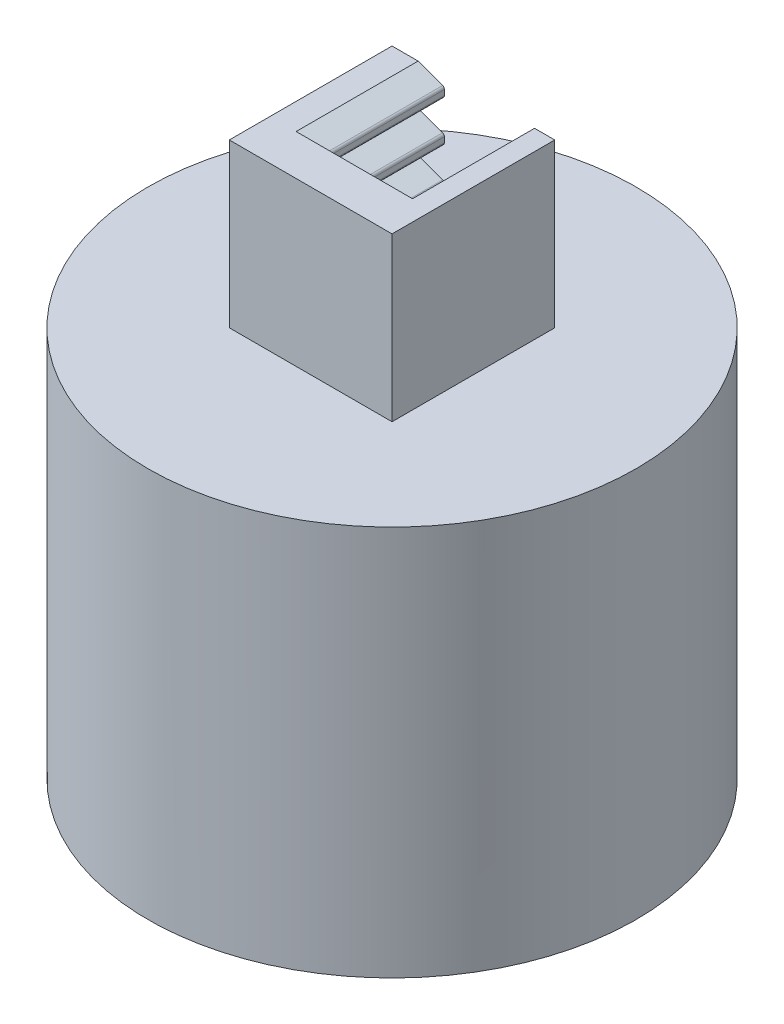
SolidWorks part; units mm, degrees
ref_plane "Front Plane" through (0, 0, 0) normal (0, 0, 1) x (1, 0, 0)
ref_plane "Top Plane" through (0, 0, 0) normal (0, 1, 0) x (1, 0, 0)
ref_plane "Right Plane" through (0, 0, 0) normal (1, 0, 0) x (0, 0, -1)
sketch "Sketch1" plane through (0, 0, 0) normal (0, 1, 0) x (1, 0, 0)
  circle A0 centre (0, 0) radius 15
  circle A1 centre (0, 0) radius 13
  dimension "D1" = 26
  dimension "D2" = 30
extrude "Boss-Extrude1" add sketch "Sketch1" along normal blind 20
sketch "Sketch2" plane through (0, 20, 0) normal (0, 1, 0) x (1, 0, 0)
  circle A0 centre (0, 0) radius 15
extrude "Boss-Extrude2" add sketch "Sketch2" along normal blind 4
sketch "Sketch4" plane through (0, 24, 0) normal (0, 1, 0) x (1, 0, 0)
  line L0 (0, 5) -> (0, -5) construction
  line L1 (-5, 5) -> (5, 5)
  line L2 (-5, 5) -> (-5, -5)
  line L3 (-5, -5) -> (5, -5)
  line L4 (5, 5) -> (5, -5)
  line L5 (-5, 0) -> (5, 0) construction
  dimension "D1" = 10
  dimension "D2" = 10
extrude "Boss-Extrude3" add sketch "Sketch4" along normal blind 10
sketch "Sketch6" plane through (0, 0, -5) normal (0, 0, -1) x (-1, 0, 0)
  line L1 (-5, 34) -> (5, 34) construction
  line L3 (-3.7584, 34) -> (3.3958, 34)
  line L4 (-3.7584, 24) -> (3.5416, 24)
  line L405 (2.1355, 274) -> (0.2416, 274)
  line L406 (0.2416, 274) -> (0.2416, 34)
  line L407 (0.2416, 34) -> (-1.7584, 34)
  line L408 (-1.7584, 34) -> (-1.7584, 274)
  line L409 (-1.7584, 274) -> (-3.7584, 274)
  line L410 (-3.7584, 274) -> (-3.7584, 24)
  line L411 (-3.7584, 24) -> (3.5416, 24)
  line L412 (3.5416, 24) -> (3.5416, 24.6743)
  line L413 (3.5416, 24.6743) -> (1.8918, 25.2748)
  line L414 (1.7816, 25.432) -> (1.7816, 25.7555)
  line L415 (1.8918, 25.9128) -> (3.5416, 26.5133)
  line L416 (3.5416, 26.5133) -> (3.5416, 27.1876)
  line L417 (3.5416, 27.1876) -> (1.8918, 27.7881)
  line L418 (1.7816, 27.9453) -> (1.7816, 28.2688)
  line L419 (1.8918, 28.426) -> (3.5416, 29.0265)
  line L420 (3.5416, 29.0265) -> (3.5416, 29.7008)
  line L421 (3.5416, 29.7008) -> (1.8918, 30.3013)
  line L422 (1.7816, 30.4586) -> (1.7816, 30.7821)
  line L423 (1.8918, 30.9393) -> (3.5416, 31.5398)
  line L424 (3.5416, 31.5398) -> (3.5416, 32.2141)
  line L425 (3.5416, 32.2141) -> (1.8918, 32.8146)
  line L426 (1.7816, 32.9719) -> (1.7816, 33.2953)
  line L427 (1.8918, 33.4526) -> (3.5416, 34.0531)
  line L428 (3.5416, 34.0531) -> (3.5416, 34.7274)
  line L429 (3.5416, 34.7274) -> (1.8918, 35.3279)
  line L430 (1.7816, 35.4851) -> (1.7816, 35.8086)
  line L431 (1.8918, 35.9658) -> (3.5416, 36.5664)
  line L432 (3.5416, 36.5664) -> (3.5416, 37.2406)
  line L433 (3.5416, 37.2406) -> (1.8918, 37.8412)
  line L434 (1.7816, 37.9984) -> (1.7816, 38.3219)
  line L435 (1.8918, 38.4791) -> (3.5416, 39.0796)
  line L436 (3.5416, 39.0796) -> (3.5416, 39.7539)
  line L437 (3.5416, 39.7539) -> (1.8918, 40.3544)
  line L438 (1.7816, 40.5117) -> (1.7816, 40.8351)
  line L439 (1.8918, 40.9924) -> (3.5416, 41.5929)
  line L440 (3.5416, 41.5929) -> (3.5416, 42.2672)
  line L441 (3.5416, 42.2672) -> (1.8918, 42.8677)
  line L442 (1.7816, 43.025) -> (1.7816, 43.3484)
  line L443 (1.8918, 43.5057) -> (3.5416, 44.1062)
  line L444 (3.5416, 44.1062) -> (3.5416, 44.7805)
  line L445 (3.5416, 44.7805) -> (1.8918, 45.381)
  line L446 (1.7816, 45.5382) -> (1.7816, 45.8617)
  line L447 (1.8918, 46.0189) -> (3.5416, 46.6194)
  line L448 (3.5416, 46.6194) -> (3.5416, 47.2937)
  line L449 (3.5416, 47.2937) -> (1.8918, 47.8942)
  line L450 (1.7816, 48.0515) -> (1.7816, 48.375)
  line L451 (1.8918, 48.5322) -> (3.5416, 49.1327)
  line L452 (3.5416, 49.1327) -> (3.5416, 49.807)
  line L453 (3.5416, 49.807) -> (1.8918, 50.4075)
  line L454 (1.7816, 50.5648) -> (1.7816, 50.8882)
  line L455 (1.8918, 51.0455) -> (3.5416, 51.646)
  line L456 (3.5416, 51.646) -> (3.5416, 52.3203)
  line L457 (3.5416, 52.3203) -> (1.8918, 52.9208)
  line L458 (1.7816, 53.078) -> (1.7816, 53.4015)
  line L459 (1.8918, 53.5588) -> (3.5416, 54.1593)
  line L460 (3.5416, 54.1593) -> (3.5416, 54.8335)
  line L461 (3.5416, 54.8335) -> (1.8918, 55.4341)
  line L462 (1.7816, 55.5913) -> (1.7816, 55.9148)
  line L463 (1.8918, 56.072) -> (3.5416, 56.6725)
  line L464 (3.5416, 56.6725) -> (3.5416, 57.3468)
  line L465 (3.5416, 57.3468) -> (1.8918, 57.9473)
  line L466 (1.7816, 58.1046) -> (1.7816, 58.428)
  line L467 (1.8918, 58.5853) -> (3.5416, 59.1858)
  line L468 (3.5416, 59.1858) -> (3.5416, 59.8601)
  line L469 (3.5416, 59.8601) -> (1.8918, 60.4606)
  line L470 (1.7816, 60.6179) -> (1.7816, 60.9413)
  line L471 (1.8918, 61.0986) -> (3.5416, 61.6991)
  line L472 (3.5416, 61.6991) -> (3.5416, 62.3734)
  line L473 (3.5416, 62.3734) -> (1.8918, 62.9739)
  line L474 (1.7816, 63.1311) -> (1.7816, 63.4546)
  line L475 (1.8918, 63.6118) -> (3.5416, 64.2124)
  line L476 (3.5416, 64.2124) -> (3.5416, 64.8866)
  line L477 (3.5416, 64.8866) -> (1.8918, 65.4871)
  line L478 (1.7816, 65.6444) -> (1.7816, 65.9679)
  line L479 (1.8918, 66.1251) -> (3.5416, 66.7256)
  line L480 (3.5416, 66.7256) -> (3.5416, 67.3999)
  line L481 (3.5416, 67.3999) -> (1.8918, 68.0004)
  line L482 (1.7816, 68.1577) -> (1.7816, 68.4811)
  line L483 (1.8918, 68.6384) -> (3.5416, 69.2389)
  line L484 (3.5416, 69.2389) -> (3.5416, 69.9132)
  line L485 (3.5416, 69.9132) -> (1.8918, 70.5137)
  line L486 (1.7816, 70.6709) -> (1.7816, 70.9944)
  line L487 (1.8918, 71.1517) -> (3.5416, 71.7522)
  line L488 (3.5416, 71.7522) -> (3.5416, 72.4265)
  line L489 (3.5416, 72.4265) -> (1.8918, 73.027)
  line L490 (1.7816, 73.1842) -> (1.7816, 73.5077)
  line L491 (1.8918, 73.6649) -> (3.5416, 74.2654)
  line L492 (3.5416, 74.2654) -> (3.5416, 74.9397)
  line L493 (3.5416, 74.9397) -> (1.8918, 75.5402)
  line L494 (1.7816, 75.6975) -> (1.7816, 76.0209)
  line L495 (1.8918, 76.1782) -> (3.5416, 76.7787)
  line L496 (3.5416, 76.7787) -> (3.5416, 77.453)
  line L497 (3.5416, 77.453) -> (1.8918, 78.0535)
  line L498 (1.7816, 78.2108) -> (1.7816, 78.5342)
  line L499 (1.8918, 78.6915) -> (3.5416, 79.292)
  line L500 (3.5416, 79.292) -> (3.5416, 79.9663)
  line L501 (3.5416, 79.9663) -> (1.8918, 80.5668)
  line L502 (1.7816, 80.724) -> (1.7816, 81.0475)
  line L503 (1.8918, 81.2047) -> (3.5416, 81.8053)
  line L504 (3.5416, 81.8053) -> (3.5416, 82.4795)
  line L505 (3.5416, 82.4795) -> (1.8918, 83.0801)
  line L506 (1.7816, 83.2373) -> (1.7816, 83.5608)
  line L507 (1.8918, 83.718) -> (3.5416, 84.3185)
  line L508 (3.5416, 84.3185) -> (3.5416, 84.9928)
  line L509 (3.5416, 84.9928) -> (1.8918, 85.5933)
  line L510 (1.7816, 85.7506) -> (1.7816, 86.074)
  line L511 (1.8918, 86.2313) -> (3.5416, 86.8318)
  line L512 (3.5416, 86.8318) -> (3.5416, 87.5061)
  line L513 (3.5416, 87.5061) -> (1.8918, 88.1066)
  line L514 (1.7816, 88.2638) -> (1.7816, 88.5873)
  line L515 (1.8918, 88.7446) -> (3.5416, 89.3451)
  line L516 (3.5416, 89.3451) -> (3.5416, 90.0194)
  line L517 (3.5416, 90.0194) -> (1.8918, 90.6199)
  line L518 (1.7816, 90.7771) -> (1.7816, 91.1006)
  line L519 (1.8918, 91.2578) -> (3.5416, 91.8583)
  line L520 (3.5416, 91.8583) -> (3.5416, 92.5326)
  line L521 (3.5416, 92.5326) -> (1.8918, 93.1331)
  line L522 (1.7816, 93.2904) -> (1.7816, 93.6139)
  line L523 (1.8918, 93.7711) -> (3.5416, 94.3716)
  line L524 (3.5416, 94.3716) -> (3.5416, 95.0459)
  line L525 (3.5416, 95.0459) -> (1.8918, 95.6464)
  line L526 (1.7816, 95.8037) -> (1.7816, 96.1271)
  line L527 (1.8918, 96.2844) -> (3.5416, 96.8849)
  line L528 (3.5416, 96.8849) -> (3.5416, 97.5592)
  line L529 (3.5416, 97.5592) -> (1.8918, 98.1597)
  line L530 (1.7816, 98.3169) -> (1.7816, 98.6404)
  line L531 (1.8918, 98.7976) -> (3.5416, 99.3982)
  line L532 (3.5416, 99.3982) -> (3.5416, 100.0724)
  line L533 (3.5416, 100.0724) -> (1.8918, 100.673)
  line L534 (1.7816, 100.8302) -> (1.7816, 101.1537)
  line L535 (1.8918, 101.3109) -> (3.5416, 101.9114)
  line L536 (3.5416, 101.9114) -> (3.5416, 102.5857)
  line L537 (3.5416, 102.5857) -> (1.8918, 103.1862)
  line L538 (1.7816, 103.3435) -> (1.7816, 103.6669)
  line L539 (1.8918, 103.8242) -> (3.5416, 104.4247)
  line L540 (3.5416, 104.4247) -> (3.5416, 105.099)
  line L541 (3.5416, 105.099) -> (1.8918, 105.6995)
  line L542 (1.7816, 105.8568) -> (1.7816, 106.1802)
  line L543 (1.8918, 106.3375) -> (3.5416, 106.938)
  line L544 (3.5416, 106.938) -> (3.5416, 107.6123)
  line L545 (3.5416, 107.6123) -> (1.8918, 108.2128)
  line L546 (1.7816, 108.37) -> (1.7816, 108.6935)
  line L547 (1.8918, 108.8507) -> (3.5416, 109.4512)
  line L548 (3.5416, 109.4512) -> (3.5416, 110.1255)
  line L549 (3.5416, 110.1255) -> (1.8918, 110.726)
  line L550 (1.7816, 110.8833) -> (1.7816, 111.2068)
  line L551 (1.8918, 111.364) -> (3.5416, 111.9645)
  line L552 (3.5416, 111.9645) -> (3.5416, 112.6388)
  line L553 (3.5416, 112.6388) -> (1.8918, 113.2393)
  line L554 (1.7816, 113.3966) -> (1.7816, 113.72)
  line L555 (1.8918, 113.8773) -> (3.5416, 114.4778)
  line L556 (3.5416, 114.4778) -> (3.5416, 115.1521)
  line L557 (3.5416, 115.1521) -> (1.8918, 115.7526)
  line L558 (1.7816, 115.9098) -> (1.7816, 116.2333)
  line L559 (1.8918, 116.3906) -> (3.5416, 116.9911)
  line L560 (3.5416, 116.9911) -> (3.5416, 117.6653)
  line L561 (3.5416, 117.6653) -> (1.8918, 118.2659)
  line L562 (1.7816, 118.4231) -> (1.7816, 118.7466)
  line L563 (1.8918, 118.9038) -> (3.5416, 119.5043)
  line L564 (3.5416, 119.5043) -> (3.5416, 120.1786)
  line L565 (3.5416, 120.1786) -> (1.8918, 120.7791)
  line L566 (1.7816, 120.9364) -> (1.7816, 121.2598)
  line L567 (1.8918, 121.4171) -> (3.5416, 122.0176)
  line L568 (3.5416, 122.0176) -> (3.5416, 122.6919)
  line L569 (3.5416, 122.6919) -> (1.8918, 123.2924)
  line L570 (1.7816, 123.4497) -> (1.7816, 123.7731)
  line L571 (1.8918, 123.9304) -> (3.5416, 124.5309)
  line L572 (3.5416, 124.5309) -> (3.5416, 125.2052)
  line L573 (3.5416, 125.2052) -> (1.8918, 125.8057)
  line L574 (1.7816, 125.9629) -> (1.7816, 126.2864)
  line L575 (1.8918, 126.4436) -> (3.5416, 127.0442)
  line L576 (3.5416, 127.0442) -> (3.5416, 127.7184)
  line L577 (3.5416, 127.7184) -> (1.8918, 128.3189)
  line L578 (1.7816, 128.4762) -> (1.7816, 128.7997)
  line L579 (1.8918, 128.9569) -> (3.5416, 129.5574)
  line L580 (3.5416, 129.5574) -> (3.5416, 130.2317)
  line L581 (3.5416, 130.2317) -> (1.8918, 130.8322)
  line L582 (1.7816, 130.9895) -> (1.7816, 131.3129)
  line L583 (1.8918, 131.4702) -> (3.5416, 132.0707)
  line L584 (3.5416, 132.0707) -> (3.5416, 132.745)
  line L585 (3.5416, 132.745) -> (1.8918, 133.3455)
  line L586 (1.7816, 133.5027) -> (1.7816, 133.8262)
  line L587 (1.8918, 133.9835) -> (3.5416, 134.584)
  line L588 (3.5416, 134.584) -> (3.5416, 135.2583)
  line L589 (3.5416, 135.2583) -> (1.8918, 135.8588)
  line L590 (1.7816, 136.016) -> (1.7816, 136.3395)
  line L591 (1.8918, 136.4967) -> (3.5416, 137.0972)
  line L592 (3.5416, 137.0972) -> (3.5416, 137.7715)
  line L593 (3.5416, 137.7715) -> (1.8918, 138.372)
  line L594 (1.7816, 138.5293) -> (1.7816, 138.8527)
  line L595 (1.8918, 139.01) -> (3.5416, 139.6105)
  line L596 (3.5416, 139.6105) -> (3.5416, 140.2848)
  line L597 (3.5416, 140.2848) -> (1.8918, 140.8853)
  line L598 (1.7816, 141.0426) -> (1.7816, 141.366)
  line L599 (1.8918, 141.5233) -> (3.5416, 142.1238)
  line L600 (3.5416, 142.1238) -> (3.5416, 142.7981)
  line L601 (3.5416, 142.7981) -> (1.8918, 143.3986)
  line L602 (1.7816, 143.5558) -> (1.7816, 143.8793)
  line L603 (1.8918, 144.0365) -> (3.5416, 144.6371)
  line L604 (3.5416, 144.6371) -> (3.5416, 145.3113)
  line L605 (3.5416, 145.3113) -> (1.8918, 145.9119)
  line L606 (1.7816, 146.0691) -> (1.7816, 146.3926)
  line L607 (1.8918, 146.5498) -> (3.5416, 147.1503)
  line L608 (3.5416, 147.1503) -> (3.5416, 147.8246)
  line L609 (3.5416, 147.8246) -> (1.8918, 148.4251)
  line L610 (1.7816, 148.5824) -> (1.7816, 148.9058)
  line L611 (1.8918, 149.0631) -> (3.5416, 149.6636)
  line L612 (3.5416, 149.6636) -> (3.5416, 150.3379)
  line L613 (3.5416, 150.3379) -> (1.8918, 150.9384)
  line L614 (1.7816, 151.0956) -> (1.7816, 151.4191)
  line L615 (1.8918, 151.5764) -> (3.5416, 152.1769)
  line L616 (3.5416, 152.1769) -> (3.5416, 152.8512)
  line L617 (3.5416, 152.8512) -> (1.8918, 153.4517)
  line L618 (1.7816, 153.6089) -> (1.7816, 153.9324)
  line L619 (1.8918, 154.0896) -> (3.5416, 154.6901)
  line L620 (3.5416, 154.6901) -> (3.5416, 155.3644)
  line L621 (3.5416, 155.3644) -> (1.8918, 155.9649)
  line L622 (1.7816, 156.1222) -> (1.7816, 156.4457)
  line L623 (1.8918, 156.6029) -> (3.5416, 157.2034)
  line L624 (3.5416, 157.2034) -> (3.5416, 157.8777)
  line L625 (3.5416, 157.8777) -> (1.8918, 158.4782)
  line L626 (1.7816, 158.6355) -> (1.7816, 158.9589)
  line L627 (1.8918, 159.1162) -> (3.5416, 159.7167)
  line L628 (3.5416, 159.7167) -> (3.5416, 160.391)
  line L629 (3.5416, 160.391) -> (1.8918, 160.9915)
  line L630 (1.7816, 161.1487) -> (1.7816, 161.4722)
  line L631 (1.8918, 161.6294) -> (3.5416, 162.23)
  line L632 (3.5416, 162.23) -> (3.5416, 162.9042)
  line L633 (3.5416, 162.9042) -> (1.8918, 163.5048)
  line L634 (1.7816, 163.662) -> (1.7816, 163.9855)
  line L635 (1.8918, 164.1427) -> (3.5416, 164.7432)
  line L636 (3.5416, 164.7432) -> (3.5416, 165.4175)
  line L637 (3.5416, 165.4175) -> (1.8918, 166.018)
  line L638 (1.7816, 166.1753) -> (1.7816, 166.4987)
  line L639 (1.8918, 166.656) -> (3.5416, 167.2565)
  line L640 (3.5416, 167.2565) -> (3.5416, 167.9308)
  line L641 (3.5416, 167.9308) -> (1.8918, 168.5313)
  line L642 (1.7816, 168.6886) -> (1.7816, 169.012)
  line L643 (1.8918, 169.1693) -> (3.5416, 169.7698)
  line L644 (3.5416, 169.7698) -> (3.5416, 170.4441)
  line L645 (3.5416, 170.4441) -> (1.8918, 171.0446)
  line L646 (1.7816, 171.2018) -> (1.7816, 171.5253)
  line L647 (1.8918, 171.6825) -> (3.5416, 172.283)
  line L648 (3.5416, 172.283) -> (3.5416, 172.9573)
  line L649 (3.5416, 172.9573) -> (1.8918, 173.5578)
  line L650 (1.7816, 173.7151) -> (1.7816, 174.0386)
  line L651 (1.8918, 174.1958) -> (3.5416, 174.7963)
  line L652 (3.5416, 174.7963) -> (3.5416, 175.4706)
  line L653 (3.5416, 175.4706) -> (1.8918, 176.0711)
  line L654 (1.7816, 176.2284) -> (1.7816, 176.5518)
  line L655 (1.8918, 176.7091) -> (3.5416, 177.3096)
  line L656 (3.5416, 177.3096) -> (3.5416, 177.9839)
  line L657 (3.5416, 177.9839) -> (1.8918, 178.5844)
  line L658 (1.7816, 178.7416) -> (1.7816, 179.0651)
  line L659 (1.8918, 179.2224) -> (3.5416, 179.8229)
  line L660 (3.5416, 179.8229) -> (3.5416, 180.4971)
  line L661 (3.5416, 180.4971) -> (1.8918, 181.0977)
  line L662 (1.7816, 181.2549) -> (1.7816, 181.5784)
  line L663 (1.8918, 181.7356) -> (3.5416, 182.3361)
  line L664 (3.5416, 182.3361) -> (3.5416, 183.0104)
  line L665 (3.5416, 183.0104) -> (1.8918, 183.6109)
  line L666 (1.7816, 183.7682) -> (1.7816, 184.0916)
  line L667 (1.8918, 184.2489) -> (3.5416, 184.8494)
  line L668 (3.5416, 184.8494) -> (3.5416, 185.5237)
  line L669 (3.5416, 185.5237) -> (1.8918, 186.1242)
  line L670 (1.7816, 186.2815) -> (1.7816, 186.6049)
  line L671 (1.8918, 186.7622) -> (3.5416, 187.3627)
  line L672 (3.5416, 187.3627) -> (3.5416, 188.037)
  line L673 (3.5416, 188.037) -> (1.8918, 188.6375)
  line L674 (1.7816, 188.7947) -> (1.7816, 189.1182)
  line L675 (1.8918, 189.2754) -> (3.5416, 189.876)
  line L676 (3.5416, 189.876) -> (3.5416, 190.5502)
  line L677 (3.5416, 190.5502) -> (1.8918, 191.1507)
  line L678 (1.7816, 191.308) -> (1.7816, 191.6315)
  line L679 (1.8918, 191.7887) -> (3.5416, 192.3892)
  line L680 (3.5416, 192.3892) -> (3.5416, 193.0635)
  line L681 (3.5416, 193.0635) -> (1.8918, 193.664)
  line L682 (1.7816, 193.8213) -> (1.7816, 194.1447)
  line L683 (1.8918, 194.302) -> (3.5416, 194.9025)
  line L684 (3.5416, 194.9025) -> (3.5416, 195.5768)
  line L685 (3.5416, 195.5768) -> (1.8918, 196.1773)
  line L686 (1.7816, 196.3345) -> (1.7816, 196.658)
  line L687 (1.8918, 196.8153) -> (3.5416, 197.4158)
  line L688 (3.5416, 197.4158) -> (3.5416, 198.0901)
  line L689 (3.5416, 198.0901) -> (1.8918, 198.6906)
  line L690 (1.7816, 198.8478) -> (1.7816, 199.1713)
  line L691 (1.8918, 199.3285) -> (3.5416, 199.929)
  line L692 (3.5416, 199.929) -> (3.5416, 200.6033)
  line L693 (3.5416, 200.6033) -> (1.8918, 201.2038)
  line L694 (1.7816, 201.3611) -> (1.7816, 201.6845)
  line L695 (1.8918, 201.8418) -> (3.5416, 202.4423)
  line L696 (3.5416, 202.4423) -> (3.5416, 203.1166)
  line L697 (3.5416, 203.1166) -> (1.8918, 203.7171)
  line L698 (1.7816, 203.8744) -> (1.7816, 204.1978)
  line L699 (1.8918, 204.3551) -> (3.5416, 204.9556)
  line L700 (3.5416, 204.9556) -> (3.5416, 205.6299)
  line L701 (3.5416, 205.6299) -> (1.8918, 206.2304)
  line L702 (1.7816, 206.3876) -> (1.7816, 206.7111)
  line L703 (1.8918, 206.8683) -> (3.5416, 207.4689)
  line L704 (3.5416, 207.4689) -> (3.5416, 208.1431)
  line L705 (3.5416, 208.1431) -> (1.8918, 208.7437)
  line L706 (1.7816, 208.9009) -> (1.7816, 209.2244)
  line L707 (1.8918, 209.3816) -> (3.5416, 209.9821)
  line L708 (3.5416, 209.9821) -> (3.5416, 210.6564)
  line L709 (3.5416, 210.6564) -> (1.8918, 211.2569)
  line L710 (1.7816, 211.4142) -> (1.7816, 211.7376)
  line L711 (1.8918, 211.8949) -> (3.5416, 212.4954)
  line L712 (3.5416, 212.4954) -> (3.5416, 213.1697)
  line L713 (3.5416, 213.1697) -> (1.8918, 213.7702)
  line L714 (1.7816, 213.9274) -> (1.7816, 214.2509)
  line L715 (1.8918, 214.4082) -> (3.5416, 215.0087)
  line L716 (3.5416, 215.0087) -> (3.5416, 215.683)
  line L717 (3.5416, 215.683) -> (1.8918, 216.2835)
  line L718 (1.7816, 216.4407) -> (1.7816, 216.7642)
  line L719 (1.8918, 216.9214) -> (3.5416, 217.5219)
  line L720 (3.5416, 217.5219) -> (3.5416, 218.1962)
  line L721 (3.5416, 218.1962) -> (1.8918, 218.7967)
  line L722 (1.7816, 218.954) -> (1.7816, 219.2775)
  line L723 (1.8918, 219.4347) -> (3.5416, 220.0352)
  line L724 (3.5416, 220.0352) -> (3.5416, 220.7095)
  line L725 (3.5416, 220.7095) -> (1.8918, 221.31)
  line L726 (1.7816, 221.4673) -> (1.7816, 221.7907)
  line L727 (1.8918, 221.948) -> (3.5416, 222.5485)
  line L728 (3.5416, 222.5485) -> (3.5416, 223.2228)
  line L729 (3.5416, 223.2228) -> (1.8918, 223.8233)
  line L730 (1.7816, 223.9805) -> (1.7816, 224.304)
  line L731 (1.8918, 224.4612) -> (3.5416, 225.0618)
  line L732 (3.5416, 225.0618) -> (3.5416, 225.736)
  line L733 (3.5416, 225.736) -> (1.8918, 226.3366)
  line L734 (1.7816, 226.4938) -> (1.7816, 226.8173)
  line L735 (1.8918, 226.9745) -> (3.5416, 227.575)
  line L736 (3.5416, 227.575) -> (3.5416, 228.2493)
  line L737 (3.5416, 228.2493) -> (1.8918, 228.8498)
  line L738 (1.7816, 229.0071) -> (1.7816, 229.3305)
  line L739 (1.8918, 229.4878) -> (3.5416, 230.0883)
  line L740 (3.5416, 230.0883) -> (3.5416, 230.7626)
  line L741 (3.5416, 230.7626) -> (1.8918, 231.3631)
  line L742 (1.7816, 231.5204) -> (1.7816, 231.8438)
  line L743 (1.8918, 232.0011) -> (3.5416, 232.6016)
  line L744 (3.5416, 232.6016) -> (3.5416, 233.2759)
  line L745 (3.5416, 233.2759) -> (1.8918, 233.8764)
  line L746 (1.7816, 234.0336) -> (1.7816, 234.3571)
  line L747 (1.8918, 234.5143) -> (3.5416, 235.1148)
  line L748 (3.5416, 235.1148) -> (3.5416, 235.7891)
  line L749 (3.5416, 235.7891) -> (1.8918, 236.3896)
  line L750 (1.7816, 236.5469) -> (1.7816, 236.8704)
  line L751 (1.8918, 237.0276) -> (3.5416, 237.6281)
  line L752 (3.5416, 237.6281) -> (3.5416, 238.3024)
  line L753 (3.5416, 238.3024) -> (1.8918, 238.9029)
  line L754 (1.7816, 239.0602) -> (1.7816, 239.3836)
  line L755 (1.8918, 239.5409) -> (3.5416, 240.1414)
  line L756 (3.5416, 240.1414) -> (3.5416, 240.8157)
  line L757 (3.5416, 240.8157) -> (1.8918, 241.4162)
  line L758 (1.7816, 241.5734) -> (1.7816, 241.8969)
  line L759 (1.8918, 242.0542) -> (3.5416, 242.6547)
  line L760 (3.5416, 242.6547) -> (3.5416, 243.3289)
  line L761 (3.5416, 243.3289) -> (1.8918, 243.9295)
  line L762 (1.7816, 244.0867) -> (1.7816, 244.4102)
  line L763 (1.8918, 244.5674) -> (3.5416, 245.1679)
  line L764 (3.5416, 245.1679) -> (3.5416, 245.8422)
  line L765 (3.5416, 245.8422) -> (1.8918, 246.4427)
  line L766 (1.7816, 246.6) -> (1.7816, 246.9234)
  line L767 (1.8918, 247.0807) -> (3.5416, 247.6812)
  line L768 (3.5416, 247.6812) -> (3.5416, 248.3555)
  line L769 (3.5416, 248.3555) -> (1.8918, 248.956)
  line L770 (1.7816, 249.1133) -> (1.7816, 249.4367)
  line L771 (1.8918, 249.594) -> (3.5416, 250.1945)
  line L772 (3.5416, 250.1945) -> (3.5416, 250.8688)
  line L773 (3.5416, 250.8688) -> (1.8918, 251.4693)
  line L774 (1.7816, 251.6265) -> (1.7816, 251.95)
  line L775 (1.8918, 252.1072) -> (3.5416, 252.7078)
  line L776 (3.5416, 252.7078) -> (3.5416, 253.382)
  line L777 (3.5416, 253.382) -> (1.8918, 253.9825)
  line L778 (1.7816, 254.1398) -> (1.7816, 254.4633)
  line L779 (1.8918, 254.6205) -> (3.5416, 255.221)
  line L780 (3.5416, 255.221) -> (3.5416, 255.8953)
  line L781 (3.5416, 255.8953) -> (1.8918, 256.4958)
  line L782 (1.7816, 256.6531) -> (1.7816, 256.9765)
  line L783 (1.8918, 257.1338) -> (3.5416, 257.7343)
  line L784 (3.5416, 257.7343) -> (3.5416, 258.4086)
  line L785 (3.5416, 258.4086) -> (1.8918, 259.0091)
  line L786 (1.7816, 259.1663) -> (1.7816, 259.4898)
  line L787 (1.8918, 259.6471) -> (3.5416, 260.2476)
  line L788 (3.5416, 260.2476) -> (3.5416, 260.9219)
  line L789 (3.5416, 260.9219) -> (1.8918, 261.5224)
  line L790 (1.7816, 261.6796) -> (1.7816, 262.0031)
  line L791 (1.8918, 262.1603) -> (3.5416, 262.7608)
  line L792 (3.5416, 262.7608) -> (3.5416, 263.4351)
  line L793 (3.5416, 263.4351) -> (1.8918, 264.0356)
  line L794 (1.7816, 264.1929) -> (1.7816, 264.5163)
  line L795 (1.8918, 264.6736) -> (3.5416, 265.2741)
  line L796 (3.5416, 265.2741) -> (3.5416, 265.9484)
  line L797 (3.5416, 265.9484) -> (1.8918, 266.5489)
  line L798 (1.7816, 266.7062) -> (1.7816, 267.0296)
  line L799 (1.8918, 267.1869) -> (3.5416, 267.7874)
  line L800 (3.5416, 267.7874) -> (3.5416, 268.4617)
  line L801 (3.5416, 268.4617) -> (1.8918, 269.0622)
  line L802 (1.7816, 269.2194) -> (1.7816, 269.5429)
  line L803 (1.8918, 269.7001) -> (3.5416, 270.3007)
  line L804 (3.5416, 270.3007) -> (3.5416, 270.9749)
  line L805 (3.5416, 270.9749) -> (1.8918, 271.5755)
  line L806 (1.7816, 271.7327) -> (1.7816, 272.0562)
  line L807 (1.8918, 272.2134) -> (3.5416, 272.8139)
  line L808 (3.5416, 272.8139) -> (3.5416, 273.4882)
  line L809 (3.5416, 273.4882) -> (2.1355, 274)
  line L815 (-3.7584, 34) -> (-3.7584, 24)
  line L816 (-3.7584, 24) -> (3.5416, 24)
  line L817 (3.5416, 24) -> (3.5416, 24.6743)
  line L818 (3.5416, 24.6743) -> (1.8918, 25.2748)
  line L819 (1.7816, 25.432) -> (1.7816, 25.7555)
  line L820 (1.8918, 25.9128) -> (3.5416, 26.5133)
  line L821 (3.5416, 26.5133) -> (3.5416, 27.1876)
  line L822 (3.5416, 27.1876) -> (1.8918, 27.7881)
  line L823 (1.7816, 27.9453) -> (1.7816, 28.2688)
  line L824 (1.8918, 28.426) -> (3.5416, 29.0265)
  line L825 (3.5416, 29.0265) -> (3.5416, 29.7008)
  line L826 (3.5416, 29.7008) -> (1.8918, 30.3013)
  line L827 (1.7816, 30.4586) -> (1.7816, 30.7821)
  line L828 (1.8918, 30.9393) -> (3.5416, 31.5398)
  line L829 (3.5416, 31.5398) -> (3.5416, 32.2141)
  line L830 (3.5416, 32.2141) -> (1.8918, 32.8146)
  line L831 (1.7816, 32.9719) -> (1.7816, 33.2953)
  line L832 (1.8918, 33.4526) -> (3.3958, 34)
  arc A198 (1.7816, 25.432) -> (1.8918, 25.2748) centre (1.949, 25.432) ccw
  arc A199 (1.8918, 25.9128) -> (1.7816, 25.7555) centre (1.949, 25.7555) ccw
  arc A200 (1.7816, 27.9453) -> (1.8918, 27.7881) centre (1.949, 27.9453) ccw
  arc A201 (1.8918, 28.426) -> (1.7816, 28.2688) centre (1.949, 28.2688) ccw
  arc A202 (1.7816, 30.4586) -> (1.8918, 30.3013) centre (1.949, 30.4586) ccw
  arc A203 (1.8918, 30.9393) -> (1.7816, 30.7821) centre (1.949, 30.7821) ccw
  arc A204 (1.7816, 32.9719) -> (1.8918, 32.8146) centre (1.949, 32.9719) ccw
  arc A205 (1.8918, 33.4526) -> (1.7816, 33.2953) centre (1.949, 33.2953) ccw
  arc A206 (1.7816, 35.4851) -> (1.8918, 35.3279) centre (1.949, 35.4851) ccw
  arc A207 (1.8918, 35.9658) -> (1.7816, 35.8086) centre (1.949, 35.8086) ccw
  arc A208 (1.7816, 37.9984) -> (1.8918, 37.8412) centre (1.949, 37.9984) ccw
  arc A209 (1.8918, 38.4791) -> (1.7816, 38.3219) centre (1.949, 38.3219) ccw
  arc A210 (1.7816, 40.5117) -> (1.8918, 40.3544) centre (1.949, 40.5117) ccw
  arc A211 (1.8918, 40.9924) -> (1.7816, 40.8351) centre (1.949, 40.8351) ccw
  arc A212 (1.7816, 43.025) -> (1.8918, 42.8677) centre (1.949, 43.025) ccw
  arc A213 (1.8918, 43.5057) -> (1.7816, 43.3484) centre (1.949, 43.3484) ccw
  arc A214 (1.7816, 45.5382) -> (1.8918, 45.381) centre (1.949, 45.5382) ccw
  arc A215 (1.8918, 46.0189) -> (1.7816, 45.8617) centre (1.949, 45.8617) ccw
  arc A216 (1.7816, 48.0515) -> (1.8918, 47.8942) centre (1.949, 48.0515) ccw
  arc A217 (1.8918, 48.5322) -> (1.7816, 48.375) centre (1.949, 48.375) ccw
  arc A218 (1.7816, 50.5648) -> (1.8918, 50.4075) centre (1.949, 50.5648) ccw
  arc A219 (1.8918, 51.0455) -> (1.7816, 50.8882) centre (1.949, 50.8882) ccw
  arc A220 (1.7816, 53.078) -> (1.8918, 52.9208) centre (1.949, 53.078) ccw
  arc A221 (1.8918, 53.5588) -> (1.7816, 53.4015) centre (1.949, 53.4015) ccw
  arc A222 (1.7816, 55.5913) -> (1.8918, 55.4341) centre (1.949, 55.5913) ccw
  arc A223 (1.8918, 56.072) -> (1.7816, 55.9148) centre (1.949, 55.9148) ccw
  arc A224 (1.7816, 58.1046) -> (1.8918, 57.9473) centre (1.949, 58.1046) ccw
  arc A225 (1.8918, 58.5853) -> (1.7816, 58.428) centre (1.949, 58.428) ccw
  arc A226 (1.7816, 60.6179) -> (1.8918, 60.4606) centre (1.949, 60.6179) ccw
  arc A227 (1.8918, 61.0986) -> (1.7816, 60.9413) centre (1.949, 60.9413) ccw
  arc A228 (1.7816, 63.1311) -> (1.8918, 62.9739) centre (1.949, 63.1311) ccw
  arc A229 (1.8918, 63.6118) -> (1.7816, 63.4546) centre (1.949, 63.4546) ccw
  arc A230 (1.7816, 65.6444) -> (1.8918, 65.4871) centre (1.949, 65.6444) ccw
  arc A231 (1.8918, 66.1251) -> (1.7816, 65.9679) centre (1.949, 65.9679) ccw
  arc A232 (1.7816, 68.1577) -> (1.8918, 68.0004) centre (1.949, 68.1577) ccw
  arc A233 (1.8918, 68.6384) -> (1.7816, 68.4811) centre (1.949, 68.4811) ccw
  arc A234 (1.7816, 70.6709) -> (1.8918, 70.5137) centre (1.949, 70.6709) ccw
  arc A235 (1.8918, 71.1517) -> (1.7816, 70.9944) centre (1.949, 70.9944) ccw
  arc A236 (1.7816, 73.1842) -> (1.8918, 73.027) centre (1.949, 73.1842) ccw
  arc A237 (1.8918, 73.6649) -> (1.7816, 73.5077) centre (1.949, 73.5077) ccw
  arc A238 (1.7816, 75.6975) -> (1.8918, 75.5402) centre (1.949, 75.6975) ccw
  arc A239 (1.8918, 76.1782) -> (1.7816, 76.0209) centre (1.949, 76.0209) ccw
  arc A240 (1.7816, 78.2108) -> (1.8918, 78.0535) centre (1.949, 78.2108) ccw
  arc A241 (1.8918, 78.6915) -> (1.7816, 78.5342) centre (1.949, 78.5342) ccw
  arc A242 (1.7816, 80.724) -> (1.8918, 80.5668) centre (1.949, 80.724) ccw
  arc A243 (1.8918, 81.2047) -> (1.7816, 81.0475) centre (1.949, 81.0475) ccw
  arc A244 (1.7816, 83.2373) -> (1.8918, 83.0801) centre (1.949, 83.2373) ccw
  arc A245 (1.8918, 83.718) -> (1.7816, 83.5608) centre (1.949, 83.5608) ccw
  arc A246 (1.7816, 85.7506) -> (1.8918, 85.5933) centre (1.949, 85.7506) ccw
  arc A247 (1.8918, 86.2313) -> (1.7816, 86.074) centre (1.949, 86.074) ccw
  arc A248 (1.7816, 88.2638) -> (1.8918, 88.1066) centre (1.949, 88.2638) ccw
  arc A249 (1.8918, 88.7446) -> (1.7816, 88.5873) centre (1.949, 88.5873) ccw
  arc A250 (1.7816, 90.7771) -> (1.8918, 90.6199) centre (1.949, 90.7771) ccw
  arc A251 (1.8918, 91.2578) -> (1.7816, 91.1006) centre (1.949, 91.1006) ccw
  arc A252 (1.7816, 93.2904) -> (1.8918, 93.1331) centre (1.949, 93.2904) ccw
  arc A253 (1.8918, 93.7711) -> (1.7816, 93.6139) centre (1.949, 93.6139) ccw
  arc A254 (1.7816, 95.8037) -> (1.8918, 95.6464) centre (1.949, 95.8037) ccw
  arc A255 (1.8918, 96.2844) -> (1.7816, 96.1271) centre (1.949, 96.1271) ccw
  arc A256 (1.7816, 98.3169) -> (1.8918, 98.1597) centre (1.949, 98.3169) ccw
  arc A257 (1.8918, 98.7976) -> (1.7816, 98.6404) centre (1.949, 98.6404) ccw
  arc A258 (1.7816, 100.8302) -> (1.8918, 100.673) centre (1.949, 100.8302) ccw
  arc A259 (1.8918, 101.3109) -> (1.7816, 101.1537) centre (1.949, 101.1537) ccw
  arc A260 (1.7816, 103.3435) -> (1.8918, 103.1862) centre (1.949, 103.3435) ccw
  arc A261 (1.8918, 103.8242) -> (1.7816, 103.6669) centre (1.949, 103.6669) ccw
  arc A262 (1.7816, 105.8568) -> (1.8918, 105.6995) centre (1.949, 105.8568) ccw
  arc A263 (1.8918, 106.3375) -> (1.7816, 106.1802) centre (1.949, 106.1802) ccw
  arc A264 (1.7816, 108.37) -> (1.8918, 108.2128) centre (1.949, 108.37) ccw
  arc A265 (1.8918, 108.8507) -> (1.7816, 108.6935) centre (1.949, 108.6935) ccw
  arc A266 (1.7816, 110.8833) -> (1.8918, 110.726) centre (1.949, 110.8833) ccw
  arc A267 (1.8918, 111.364) -> (1.7816, 111.2068) centre (1.949, 111.2068) ccw
  arc A268 (1.7816, 113.3966) -> (1.8918, 113.2393) centre (1.949, 113.3966) ccw
  arc A269 (1.8918, 113.8773) -> (1.7816, 113.72) centre (1.949, 113.72) ccw
  arc A270 (1.7816, 115.9098) -> (1.8918, 115.7526) centre (1.949, 115.9098) ccw
  arc A271 (1.8918, 116.3906) -> (1.7816, 116.2333) centre (1.949, 116.2333) ccw
  arc A272 (1.7816, 118.4231) -> (1.8918, 118.2659) centre (1.949, 118.4231) ccw
  arc A273 (1.8918, 118.9038) -> (1.7816, 118.7466) centre (1.949, 118.7466) ccw
  arc A274 (1.7816, 120.9364) -> (1.8918, 120.7791) centre (1.949, 120.9364) ccw
  arc A275 (1.8918, 121.4171) -> (1.7816, 121.2598) centre (1.949, 121.2598) ccw
  arc A276 (1.7816, 123.4497) -> (1.8918, 123.2924) centre (1.949, 123.4497) ccw
  arc A277 (1.8918, 123.9304) -> (1.7816, 123.7731) centre (1.949, 123.7731) ccw
  arc A278 (1.7816, 125.9629) -> (1.8918, 125.8057) centre (1.949, 125.9629) ccw
  arc A279 (1.8918, 126.4436) -> (1.7816, 126.2864) centre (1.949, 126.2864) ccw
  arc A280 (1.7816, 128.4762) -> (1.8918, 128.3189) centre (1.949, 128.4762) ccw
  arc A281 (1.8918, 128.9569) -> (1.7816, 128.7997) centre (1.949, 128.7997) ccw
  arc A282 (1.7816, 130.9895) -> (1.8918, 130.8322) centre (1.949, 130.9895) ccw
  arc A283 (1.8918, 131.4702) -> (1.7816, 131.3129) centre (1.949, 131.3129) ccw
  arc A284 (1.7816, 133.5027) -> (1.8918, 133.3455) centre (1.949, 133.5027) ccw
  arc A285 (1.8918, 133.9835) -> (1.7816, 133.8262) centre (1.949, 133.8262) ccw
  arc A286 (1.7816, 136.016) -> (1.8918, 135.8588) centre (1.949, 136.016) ccw
  arc A287 (1.8918, 136.4967) -> (1.7816, 136.3395) centre (1.949, 136.3395) ccw
  arc A288 (1.7816, 138.5293) -> (1.8918, 138.372) centre (1.949, 138.5293) ccw
  arc A289 (1.8918, 139.01) -> (1.7816, 138.8527) centre (1.949, 138.8527) ccw
  arc A290 (1.7816, 141.0426) -> (1.8918, 140.8853) centre (1.949, 141.0426) ccw
  arc A291 (1.8918, 141.5233) -> (1.7816, 141.366) centre (1.949, 141.366) ccw
  arc A292 (1.7816, 143.5558) -> (1.8918, 143.3986) centre (1.949, 143.5558) ccw
  arc A293 (1.8918, 144.0365) -> (1.7816, 143.8793) centre (1.949, 143.8793) ccw
  arc A294 (1.7816, 146.0691) -> (1.8918, 145.9119) centre (1.949, 146.0691) ccw
  arc A295 (1.8918, 146.5498) -> (1.7816, 146.3926) centre (1.949, 146.3926) ccw
  arc A296 (1.7816, 148.5824) -> (1.8918, 148.4251) centre (1.949, 148.5824) ccw
  arc A297 (1.8918, 149.0631) -> (1.7816, 148.9058) centre (1.949, 148.9058) ccw
  arc A298 (1.7816, 151.0956) -> (1.8918, 150.9384) centre (1.949, 151.0956) ccw
  arc A299 (1.8918, 151.5764) -> (1.7816, 151.4191) centre (1.949, 151.4191) ccw
  arc A300 (1.7816, 153.6089) -> (1.8918, 153.4517) centre (1.949, 153.6089) ccw
  arc A301 (1.8918, 154.0896) -> (1.7816, 153.9324) centre (1.949, 153.9324) ccw
  arc A302 (1.7816, 156.1222) -> (1.8918, 155.9649) centre (1.949, 156.1222) ccw
  arc A303 (1.8918, 156.6029) -> (1.7816, 156.4457) centre (1.949, 156.4457) ccw
  arc A304 (1.7816, 158.6355) -> (1.8918, 158.4782) centre (1.949, 158.6355) ccw
  arc A305 (1.8918, 159.1162) -> (1.7816, 158.9589) centre (1.949, 158.9589) ccw
  arc A306 (1.7816, 161.1487) -> (1.8918, 160.9915) centre (1.949, 161.1487) ccw
  arc A307 (1.8918, 161.6294) -> (1.7816, 161.4722) centre (1.949, 161.4722) ccw
  arc A308 (1.7816, 163.662) -> (1.8918, 163.5048) centre (1.949, 163.662) ccw
  arc A309 (1.8918, 164.1427) -> (1.7816, 163.9855) centre (1.949, 163.9855) ccw
  arc A310 (1.7816, 166.1753) -> (1.8918, 166.018) centre (1.949, 166.1753) ccw
  arc A311 (1.8918, 166.656) -> (1.7816, 166.4987) centre (1.949, 166.4987) ccw
  arc A312 (1.7816, 168.6886) -> (1.8918, 168.5313) centre (1.949, 168.6886) ccw
  arc A313 (1.8918, 169.1693) -> (1.7816, 169.012) centre (1.949, 169.012) ccw
  arc A314 (1.7816, 171.2018) -> (1.8918, 171.0446) centre (1.949, 171.2018) ccw
  arc A315 (1.8918, 171.6825) -> (1.7816, 171.5253) centre (1.949, 171.5253) ccw
  arc A316 (1.7816, 173.7151) -> (1.8918, 173.5578) centre (1.949, 173.7151) ccw
  arc A317 (1.8918, 174.1958) -> (1.7816, 174.0386) centre (1.949, 174.0386) ccw
  arc A318 (1.7816, 176.2284) -> (1.8918, 176.0711) centre (1.949, 176.2284) ccw
  arc A319 (1.8918, 176.7091) -> (1.7816, 176.5518) centre (1.949, 176.5518) ccw
  arc A320 (1.7816, 178.7416) -> (1.8918, 178.5844) centre (1.949, 178.7416) ccw
  arc A321 (1.8918, 179.2224) -> (1.7816, 179.0651) centre (1.949, 179.0651) ccw
  arc A322 (1.7816, 181.2549) -> (1.8918, 181.0977) centre (1.949, 181.2549) ccw
  arc A323 (1.8918, 181.7356) -> (1.7816, 181.5784) centre (1.949, 181.5784) ccw
  arc A324 (1.7816, 183.7682) -> (1.8918, 183.6109) centre (1.949, 183.7682) ccw
  arc A325 (1.8918, 184.2489) -> (1.7816, 184.0916) centre (1.949, 184.0916) ccw
  arc A326 (1.7816, 186.2815) -> (1.8918, 186.1242) centre (1.949, 186.2815) ccw
  arc A327 (1.8918, 186.7622) -> (1.7816, 186.6049) centre (1.949, 186.6049) ccw
  arc A328 (1.7816, 188.7947) -> (1.8918, 188.6375) centre (1.949, 188.7947) ccw
  arc A329 (1.8918, 189.2754) -> (1.7816, 189.1182) centre (1.949, 189.1182) ccw
  arc A330 (1.7816, 191.308) -> (1.8918, 191.1507) centre (1.949, 191.308) ccw
  arc A331 (1.8918, 191.7887) -> (1.7816, 191.6315) centre (1.949, 191.6315) ccw
  arc A332 (1.7816, 193.8213) -> (1.8918, 193.664) centre (1.949, 193.8213) ccw
  arc A333 (1.8918, 194.302) -> (1.7816, 194.1447) centre (1.949, 194.1447) ccw
  arc A334 (1.7816, 196.3345) -> (1.8918, 196.1773) centre (1.949, 196.3345) ccw
  arc A335 (1.8918, 196.8153) -> (1.7816, 196.658) centre (1.949, 196.658) ccw
  arc A336 (1.7816, 198.8478) -> (1.8918, 198.6906) centre (1.949, 198.8478) ccw
  arc A337 (1.8918, 199.3285) -> (1.7816, 199.1713) centre (1.949, 199.1713) ccw
  arc A338 (1.7816, 201.3611) -> (1.8918, 201.2038) centre (1.949, 201.3611) ccw
  arc A339 (1.8918, 201.8418) -> (1.7816, 201.6845) centre (1.949, 201.6845) ccw
  arc A340 (1.7816, 203.8744) -> (1.8918, 203.7171) centre (1.949, 203.8744) ccw
  arc A341 (1.8918, 204.3551) -> (1.7816, 204.1978) centre (1.949, 204.1978) ccw
  arc A342 (1.7816, 206.3876) -> (1.8918, 206.2304) centre (1.949, 206.3876) ccw
  arc A343 (1.8918, 206.8683) -> (1.7816, 206.7111) centre (1.949, 206.7111) ccw
  arc A344 (1.7816, 208.9009) -> (1.8918, 208.7437) centre (1.949, 208.9009) ccw
  arc A345 (1.8918, 209.3816) -> (1.7816, 209.2244) centre (1.949, 209.2244) ccw
  arc A346 (1.7816, 211.4142) -> (1.8918, 211.2569) centre (1.949, 211.4142) ccw
  arc A347 (1.8918, 211.8949) -> (1.7816, 211.7376) centre (1.949, 211.7376) ccw
  arc A348 (1.7816, 213.9274) -> (1.8918, 213.7702) centre (1.949, 213.9274) ccw
  arc A349 (1.8918, 214.4082) -> (1.7816, 214.2509) centre (1.949, 214.2509) ccw
  arc A350 (1.7816, 216.4407) -> (1.8918, 216.2835) centre (1.949, 216.4407) ccw
  arc A351 (1.8918, 216.9214) -> (1.7816, 216.7642) centre (1.949, 216.7642) ccw
  arc A352 (1.7816, 218.954) -> (1.8918, 218.7967) centre (1.949, 218.954) ccw
  arc A353 (1.8918, 219.4347) -> (1.7816, 219.2775) centre (1.949, 219.2775) ccw
  arc A354 (1.7816, 221.4673) -> (1.8918, 221.31) centre (1.949, 221.4673) ccw
  arc A355 (1.8918, 221.948) -> (1.7816, 221.7907) centre (1.949, 221.7907) ccw
  arc A356 (1.7816, 223.9805) -> (1.8918, 223.8233) centre (1.949, 223.9805) ccw
  arc A357 (1.8918, 224.4612) -> (1.7816, 224.304) centre (1.949, 224.304) ccw
  arc A358 (1.7816, 226.4938) -> (1.8918, 226.3366) centre (1.949, 226.4938) ccw
  arc A359 (1.8918, 226.9745) -> (1.7816, 226.8173) centre (1.949, 226.8173) ccw
  arc A360 (1.7816, 229.0071) -> (1.8918, 228.8498) centre (1.949, 229.0071) ccw
  arc A361 (1.8918, 229.4878) -> (1.7816, 229.3305) centre (1.949, 229.3305) ccw
  arc A362 (1.7816, 231.5204) -> (1.8918, 231.3631) centre (1.949, 231.5204) ccw
  arc A363 (1.8918, 232.0011) -> (1.7816, 231.8438) centre (1.949, 231.8438) ccw
  arc A364 (1.7816, 234.0336) -> (1.8918, 233.8764) centre (1.949, 234.0336) ccw
  arc A365 (1.8918, 234.5143) -> (1.7816, 234.3571) centre (1.949, 234.3571) ccw
  arc A366 (1.7816, 236.5469) -> (1.8918, 236.3896) centre (1.949, 236.5469) ccw
  arc A367 (1.8918, 237.0276) -> (1.7816, 236.8704) centre (1.949, 236.8704) ccw
  arc A368 (1.7816, 239.0602) -> (1.8918, 238.9029) centre (1.949, 239.0602) ccw
  arc A369 (1.8918, 239.5409) -> (1.7816, 239.3836) centre (1.949, 239.3836) ccw
  arc A370 (1.7816, 241.5734) -> (1.8918, 241.4162) centre (1.949, 241.5734) ccw
  arc A371 (1.8918, 242.0542) -> (1.7816, 241.8969) centre (1.949, 241.8969) ccw
  arc A372 (1.7816, 244.0867) -> (1.8918, 243.9295) centre (1.949, 244.0867) ccw
  arc A373 (1.8918, 244.5674) -> (1.7816, 244.4102) centre (1.949, 244.4102) ccw
  arc A374 (1.7816, 246.6) -> (1.8918, 246.4427) centre (1.949, 246.6) ccw
  arc A375 (1.8918, 247.0807) -> (1.7816, 246.9234) centre (1.949, 246.9234) ccw
  arc A376 (1.7816, 249.1133) -> (1.8918, 248.956) centre (1.949, 249.1133) ccw
  arc A377 (1.8918, 249.594) -> (1.7816, 249.4367) centre (1.949, 249.4367) ccw
  arc A378 (1.7816, 251.6265) -> (1.8918, 251.4693) centre (1.949, 251.6265) ccw
  arc A379 (1.8918, 252.1072) -> (1.7816, 251.95) centre (1.949, 251.95) ccw
  arc A380 (1.7816, 254.1398) -> (1.8918, 253.9825) centre (1.949, 254.1398) ccw
  arc A381 (1.8918, 254.6205) -> (1.7816, 254.4633) centre (1.949, 254.4633) ccw
  arc A382 (1.7816, 256.6531) -> (1.8918, 256.4958) centre (1.949, 256.6531) ccw
  arc A383 (1.8918, 257.1338) -> (1.7816, 256.9765) centre (1.949, 256.9765) ccw
  arc A384 (1.7816, 259.1663) -> (1.8918, 259.0091) centre (1.949, 259.1663) ccw
  arc A385 (1.8918, 259.6471) -> (1.7816, 259.4898) centre (1.949, 259.4898) ccw
  arc A386 (1.7816, 261.6796) -> (1.8918, 261.5224) centre (1.949, 261.6796) ccw
  arc A387 (1.8918, 262.1603) -> (1.7816, 262.0031) centre (1.949, 262.0031) ccw
  arc A388 (1.7816, 264.1929) -> (1.8918, 264.0356) centre (1.949, 264.1929) ccw
  arc A389 (1.8918, 264.6736) -> (1.7816, 264.5163) centre (1.949, 264.5163) ccw
  arc A390 (1.7816, 266.7062) -> (1.8918, 266.5489) centre (1.949, 266.7062) ccw
  arc A391 (1.8918, 267.1869) -> (1.7816, 267.0296) centre (1.949, 267.0296) ccw
  arc A392 (1.7816, 269.2194) -> (1.8918, 269.0622) centre (1.949, 269.2194) ccw
  arc A393 (1.8918, 269.7001) -> (1.7816, 269.5429) centre (1.949, 269.5429) ccw
  arc A394 (1.7816, 271.7327) -> (1.8918, 271.5755) centre (1.949, 271.7327) ccw
  arc A395 (1.8918, 272.2134) -> (1.7816, 272.0562) centre (1.949, 272.0562) ccw
  arc A396 (1.7816, 25.432) -> (1.8918, 25.2748) centre (1.949, 25.432) ccw
  arc A397 (1.8918, 25.9128) -> (1.7816, 25.7555) centre (1.949, 25.7555) ccw
  arc A398 (1.7816, 27.9453) -> (1.8918, 27.7881) centre (1.949, 27.9453) ccw
  arc A399 (1.8918, 28.426) -> (1.7816, 28.2688) centre (1.949, 28.2688) ccw
  arc A400 (1.7816, 30.4586) -> (1.8918, 30.3013) centre (1.949, 30.4586) ccw
  arc A401 (1.8918, 30.9393) -> (1.7816, 30.7821) centre (1.949, 30.7821) ccw
  arc A402 (1.7816, 32.9719) -> (1.8918, 32.8146) centre (1.949, 32.9719) ccw
  arc A403 (1.8918, 33.4526) -> (1.7816, 33.2953) centre (1.949, 33.2953) ccw
  line M606 (-5, 24) -> (5, 24)
  line M608 (5, 34) -> (-5, 34)
  dimension "D1" = 0
extrude "Cut-Extrude2" cut sketch "Sketch6" against normal blind 7.5 contours A403 L832 L815 L817 L818 A396 L819 A397 L820 L821 L822 A398 L823 A399 L824 L825 L826 A400 L827 A401 L828 L829 L830 A402 L831 M608 M606
ref_plane "Plane2" through (0, 0, -15) normal (0, 0, -1) x (-1, 0, 0)
sketch "Sketch8" plane through (0, 0, -15) normal (0, 0, -1) x (-1, 0, 0)
  line L0 (-6, 12) -> (-2, 12)
  line L1 (-6, 12) -> (-6, 20)
  line L2 (-6, 20) -> (6, 20)
  line L3 (6, 12) -> (6, 20)
  line L4 (-2, 12) -> (-2, 0)
  line L5 (-2, 0) -> (2, 0)
  line L6 (2, 12) -> (2, 0)
  line L7 (2, 12) -> (6, 12)
  line L8 (-15, 0) -> (15, 0) construction
  line L10 (0, 20) -> (0, 0) construction
  line L11 (-3.7584, 24) -> (3.5416, 24) construction
  dimension "D1" = 12
  dimension "D2" = 8
  dimension "D3" = 4
  dimension "D4" = 4
extrude "Cut-Extrude3" cut sketch "Sketch8" against normal blind 5
